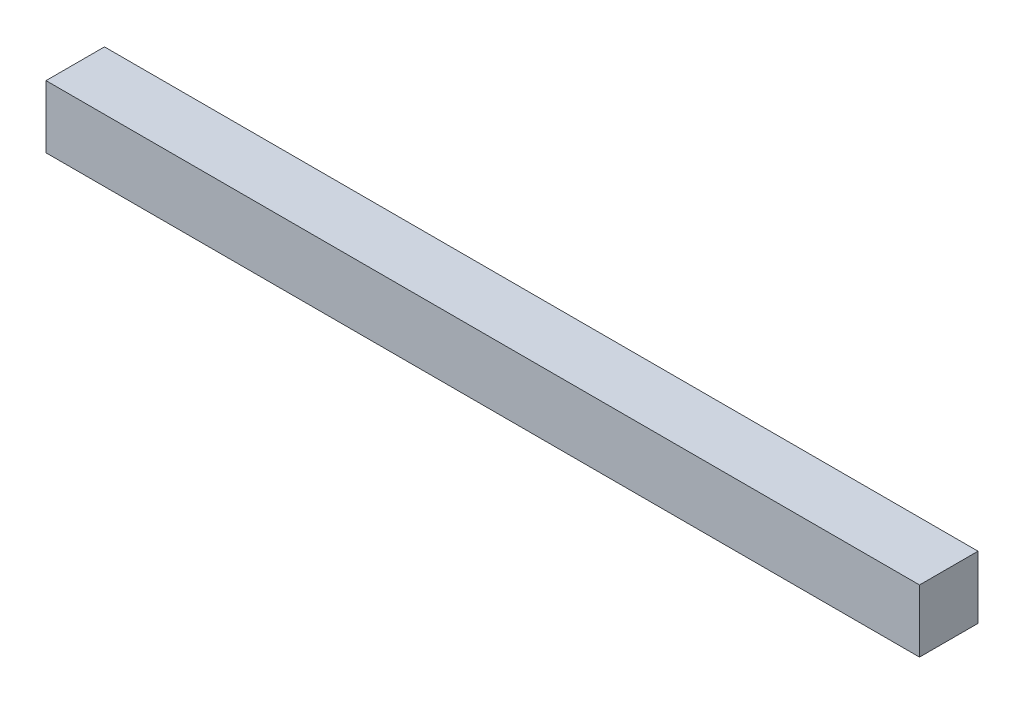
SolidWorks part; units mm, degrees
ref_plane "Płaszczyzna przednia" through (0, 0, 0) normal (0, 0, 1) x (1, 0, 0)
ref_plane "Płaszczyzna górna" through (0, 0, 0) normal (0, 1, 0) x (1, 0, 0)
ref_plane "Płaszczyzna prawa" through (0, 0, 0) normal (1, 0, 0) x (0, 0, -1)
sketch "Szkic1" plane through (0, 0, 0) normal (0, 0, 1) x (1, 0, 0)
  line L0 (-526.6982, -29.3759) -> (-526.6982, -40.0709)
  line L1 (-526.6982, -29.3759) -> (-377.3046, -29.3759)
  line L2 (-526.6982, -40.0709) -> (-377.3046, -40.0709)
  line L3 (-377.3046, -29.3759) -> (-377.3046, -40.0709)
extrude "Dodanie-wyciągnięcie1" add sketch "Szkic1" along normal blind 10
